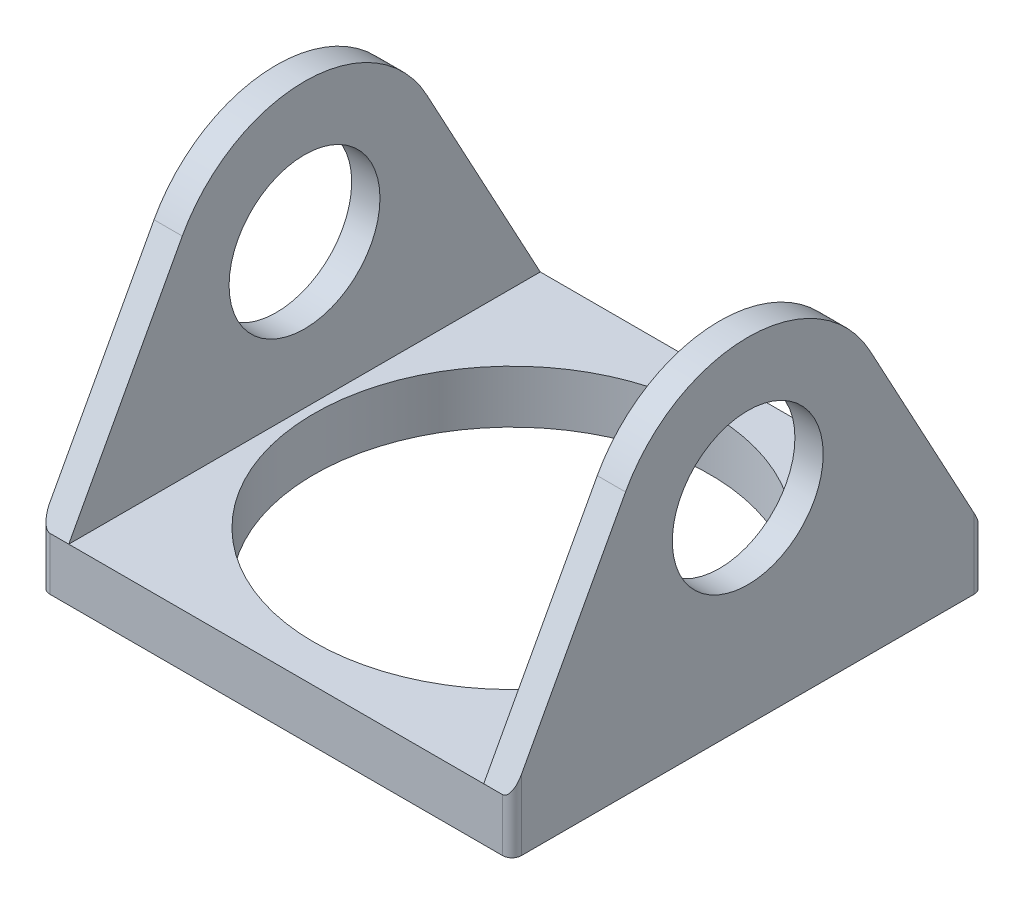
SolidWorks part; units mm, degrees
ref_plane "Front Plane" through (0, 0, 0) normal (0, 0, 1) x (1, 0, 0)
ref_plane "Top Plane" through (0, 0, 0) normal (0, 1, 0) x (1, 0, 0)
ref_plane "Right Plane" through (0, 0, 0) normal (1, 0, 0) x (0, 0, -1)
sketch "Sketch1" plane through (0, 0, 0) normal (0, 1, 0) x (1, 0, 0)
  line L1 (-125, 125) -> (125, 125)
  line L2 (-125, 125) -> (-125, -125)
  line L3 (-125, -125) -> (125, -125)
  line L4 (125, 125) -> (125, -125)
  line L5 (-125, 125) -> (125, -125) construction
  line L6 (-125, -125) -> (125, 125) construction
  point P0 (0, 0)
  dimension "D2" = 250
extrude "Boss-Extrude1" add sketch "Sketch1" along normal blind 28
sketch "Sketch2" plane through (0, 28, 0) normal (0, 1, 0) x (1, 0, 0)
  circle A0 centre (0, 0) radius 105
  dimension "D1" = 210
extrude "Cut-Extrude1" cut sketch "Sketch2" against normal up to next
sketch "Sketch3" plane through (0, 28, 0) normal (0, 1, 0) x (1, 0, 0)
  line L0 (-125, -125) -> (125, -125) construction
  line L1 (-125, 125) -> (-110, 125)
  line L2 (-125, 125) -> (-125, -125)
  line L3 (-125, -125) -> (-110, -125)
  line L4 (-110, 125) -> (-110, -125)
  line L5 (0, 125) -> (0, -125) construction
  line L6 (125, 125) -> (-125, 125) construction
  dimension "D1" = 15
extrude "Boss-Extrude2" add sketch "Sketch3" along normal blind 150
ref_plane "Plane1" through (0, 0, 0) normal (1, 0, 0) x (0, 0, -1)
mirror "Mirror1" about plane through (0, 0, 0) normal (1, 0, 0) of "Boss-Extrude2"
sketch "Sketch4" plane through (125, 0, 0) normal (1, 0, 0) x (0, 0, -1)
  line L0 (125, 28) -> (-125, 28) construction
  line L4 (125, 178) -> (125, 0) construction
  line L5 (-125, 178) -> (-125, 0) construction
  line L6 (-125, 0) -> (125, 0) construction
  line L7 (0, 28) -> (0, 178) construction
  line L8 (125, 178) -> (-125, 178) construction
  circle A0 centre (0, 104.34) radius 40
  point P17 (-7.5606, 83)
  dimension "D2" = 80
  dimension "D1" = 28
  dimension "D3" = 76.34
  dimension "D4" = 125
extrude "Cut-Extrude2" cut sketch "Sketch4" against normal through all
sketch "Sketch5" plane through (125, 0, 0) normal (1, 0, 0) x (0, 0, -1)
  line L0 (125, 28) -> (-125, 28) construction
  line L1 (125, 178) -> (125, 0) construction
  line L2 (-125, 178) -> (-125, 0) construction
  line L3 (-125, 0) -> (125, 0) construction
  line L6 (125, 178) -> (-125, 178) construction
  line L7 (125, 28) -> (64.7985, 139.3678)
  line L8 (-125, 28) -> (-64.7985, 139.3678)
  arc A0 (64.7985, 139.3678) -> (-64.7985, 139.3678) centre (0, 104.34) ccw
  circle A2 centre (0, 104.34) radius 40 construction
  point P17 (67.7494, 133.4364)
  dimension "D1" = 28
extrude "Cut-Extrude4" cut sketch "Sketch5" against normal through all and the other way through all flip side to cut
fillet "Fillet1" radius 5 4 edges at (-125, 14, 125) (125, 14, 125) (-125, 14, -125) (125, 14, -125)
